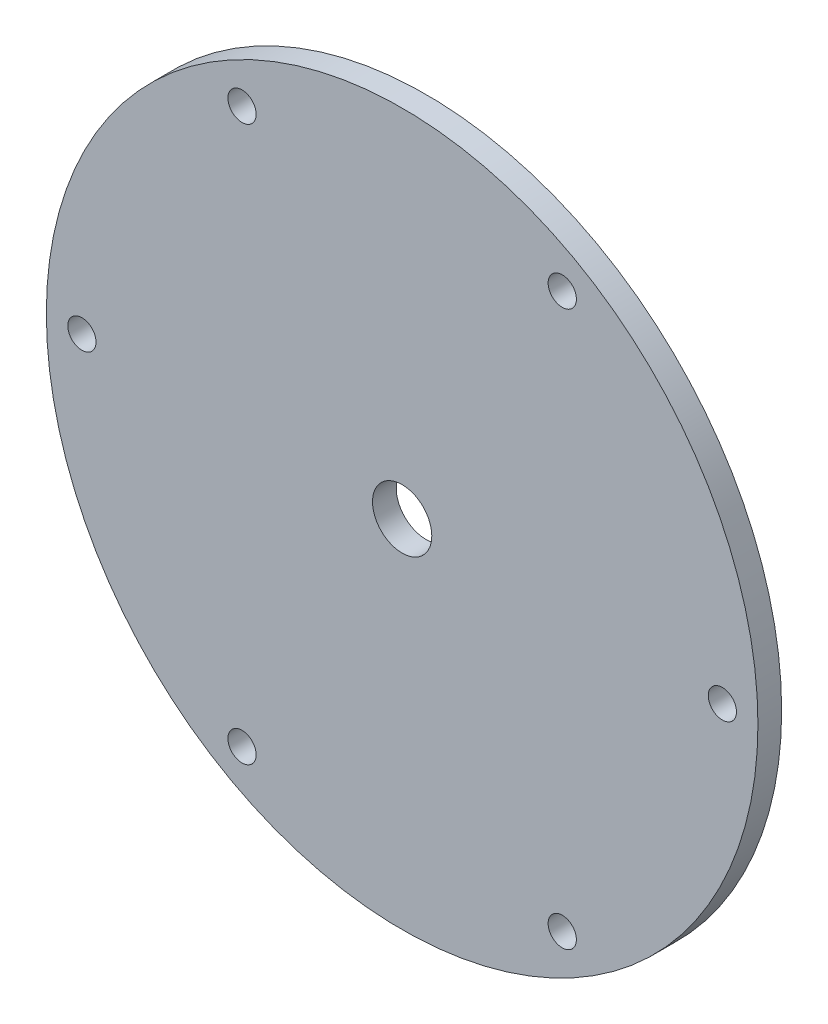
SolidWorks part; units mm, degrees
ref_plane "Front Plane" through (0, 0, 0) normal (0, 0, 1) x (1, 0, 0)
ref_plane "Top Plane" through (0, 0, 0) normal (0, 1, 0) x (1, 0, 0)
ref_plane "Right Plane" through (0, 0, 0) normal (1, 0, 0) x (0, 0, -1)
sketch "Sketch1" plane through (0, 0, 0) normal (0, 0, 1) x (1, 0, 0)
  circle A0 centre (0, 0) radius 60
  circle A1 centre (0, 0) radius 5
  point P20 (0, 0)
  point P23 (0, 0)
  dimension "D1" = 120
  dimension "D2" = 10
extrude "Boss-Extrude1" add sketch "Sketch1" along normal blind 4
hole_wizard "3/16 (0.1875) Dowel Hole1" positions "3DSketch2" profile "Sketch4" hole size "3/16" standard "ANSI Inch" end condition up to next
sketch3d "3DSketch2"
  line L0 (-39.5024, 68.4202, 4) -> (48.0499, -83.2249, 4) construction
  line L1 (-39.8539, -69.0291, 4) -> (39.8539, 69.0291, 4) construction
  line L2 (-71.0127, 0, 4) -> (88.1271, 0, 4) construction
  circle A0 centre (0, 0, 4) radius 54 construction
  point P0 (-54, 0, 4)
  point P2 (54, 0, 4)
  point P4 (-27, 46.7654, 4)
  point P6 (-27, -46.7654, 4)
  point P8 (27, 46.7654, 4)
  point P10 (27, -46.7654, 4)
  point P20 (0, 0, 58)
sketch "Sketch4" plane through (-54, 0, 4) normal (1, 0, 0) x (0, -1, 0)
  line L0 (0, 0) -> (0, 4)
  line L1 (0, 4) -> (2.3812, 4)
  line L2 (2.3812, 4) -> (2.3812, 0)
  line L5 (2.3812, 0) -> (0, 0)
  line L11 (0, -6.35) -> (0, 107.95) construction
  dimension "Thru Hole Dia." = 4.7625
  dimension "Thru Hole Depth" = 4
sketch "Sketch2" plane through (0, 0, 4) normal (0, 0, 1) x (1, 0, 0)
  line L0 (-71.0127, 0) -> (88.1271, 0) construction
  line L1 (-39.8539, -69.0291) -> (39.8539, 69.0291) construction
  line L2 (-39.5024, 68.4202) -> (48.0499, -83.2249) construction
  circle A0 centre (0, 0) radius 54
  dimension "D1" = 60
  dimension "D2" = 60
